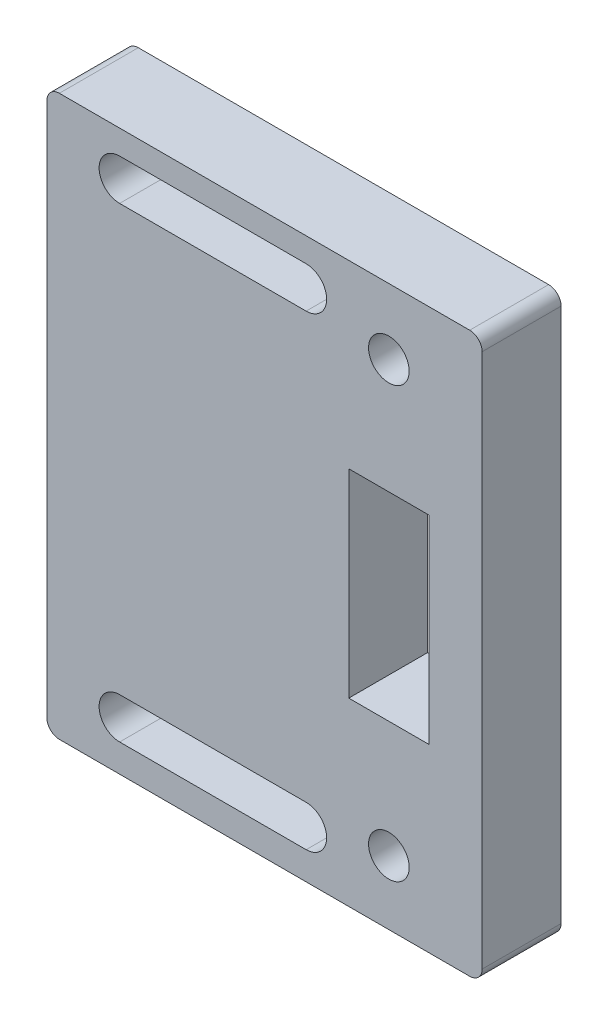
SolidWorks part; units mm, degrees
ref_plane "Front Plane" through (0, 0, 0) normal (0, 0, 1) x (1, 0, 0)
ref_plane "Top Plane" through (0, 0, 0) normal (0, 1, 0) x (1, 0, 0)
ref_plane "Right Plane" through (0, 0, 0) normal (1, 0, 0) x (0, 0, -1)
sketch "Sketch1" plane through (0, 0, 0) normal (0, 0, 1) x (1, 0, 0)
  line L0 (70, -45) -> (0, -45) construction
  line L1 (0, 0) -> (70, 0)
  line L2 (0, 0) -> (0, -90)
  line L3 (0, -90) -> (70, -90)
  line L4 (70, 0) -> (70, -90)
  line L5 (55, -45) -> (55, -29.025) construction
  line L6 (55, -29.025) -> (61.45, -29.025)
  line L7 (61.45, -29.025) -> (61.45, -60.975)
  line L8 (61.45, -60.975) -> (55, -60.975)
  line L9 (55, -60.975) -> (48.55, -60.975)
  line L10 (48.55, -60.975) -> (48.55, -29.025)
  line L11 (48.55, -29.025) -> (55, -29.025)
  line L12 (55, -45) -> (55, -60.975) construction
  line L13 (55, 0) -> (55, -13.25) construction
  line L14 (55, -90) -> (55, -79.56) construction
  point P18 (0, 0)
  point P19 (0, 0)
  dimension "D1" = 90
  dimension "D2" = 55
  dimension "D3" = 12.9
  dimension "D4" = 31.95
  dimension "D5" = 70
  dimension "D6" = 10.44
  dimension "D7" = 55
  dimension "D8" = 55
extrude "Boss-Extrude1" add sketch "Sketch1" along normal blind 12.7
sketch "Sketch4" plane through (0, 0, 0) normal (0, 0, -1) x (-1, 0, 0)
  line L0 (-55, -0.2792) -> (-55, -10.5796)
  line L2 (-55, -90) -> (-55, -79.6996)
  line L4 (-55, -79.6996) -> (-55, -10.5796) construction
  line L5 (0, 0) -> (0, -90) construction
  line L6 (0, -90) -> (-70, -90) construction
  line L9 (0, -90) -> (-70, -90) construction
  point P6 (-60, -79.6996)
  point P8 (0, 0)
  point P10 (0, 0)
  point P11 (0, 0)
  point P15 (0, 0)
  dimension "D1" = 55
  dimension "D2" = 10.3004
  dimension "D3" = 69.12
hole_wizard "CSK for 1/4 Flat Head Machine Screw1" positions "Sketch5" profile "Sketch6" countersink size "1/4" standard "ANSI Inch" end condition through all
sketch "Sketch5" plane through (0, 0, 0) normal (0, 0, -1) x (-1, 0, 0)
  point P0 (-55, -10.5796)
  point P3 (-55, -79.6996)
sketch "Sketch6" plane through (55, -10.5796, 0) normal (1, 0, 0) x (0, 1, 0)
  line L0 (0, 0) -> (0, 12.7)
  line L1 (0, 12.7) -> (3.2639, 12.7)
  line L2 (3.2639, 12.7) -> (3.2639, 3.6524)
  line L3 (3.2639, 3.6524) -> (6.4389, 0)
  line L5 (6.4389, 0) -> (0, 0)
  line L6 (-3.2639, 3.6524) -> (-6.4389, 0) construction
  line L11 (0, -6.35) -> (0, 107.95) construction
  dimension "Thru Hole Dia." = 6.5278
  dimension "Thru Hole Depth" = 12.7
  dimension "Near C'Sink Dia." = 12.8778
  dimension "Near C'Sink Angle" = 82
fillet "Fillet1" radius 2 4 edges at (0, 0, 6.35) (70, 0, 6.35) (0, -90, 6.35) (70, -90, 6.35)
sketch "Sketch7" plane through (0, 0, 0) normal (0, 0, -1) x (-1, 0, 0)
  line L0 (-41.6955, -85.5134) -> (-11.6955, -85.5134)
  line L1 (-11.6955, -78.9134) -> (-41.6955, -78.9134)
  line L2 (-11.6955, -78.9134) -> (-11.6955, -10.4934) construction
  line L3 (-11.6955, -10.4934) -> (-41.6955, -10.4934)
  line L4 (-11.6955, -3.8934) -> (-41.6955, -3.8934)
  arc A0 (-11.6955, -85.5134) -> (-11.6955, -78.9134) centre (-11.6955, -82.2134) ccw
  arc A1 (-41.6955, -78.9134) -> (-41.6955, -85.5134) centre (-41.6955, -82.2134) ccw
  arc A2 (-11.6955, -10.4934) -> (-11.6955, -3.8934) centre (-11.6955, -7.1934) ccw
  arc A3 (-41.6955, -3.8934) -> (-41.6955, -10.4934) centre (-41.6955, -7.1934) ccw
  dimension "D1" = 3.3
  dimension "D4" = 3.3
  dimension "D2" = 30
  dimension "D3" = 68.42
  dimension "D5" = 30
extrude "Cut-Extrude1" cut sketch "Sketch7" against normal through all contours A1 L0 A0 L1 | A3 L3 A2 L4
